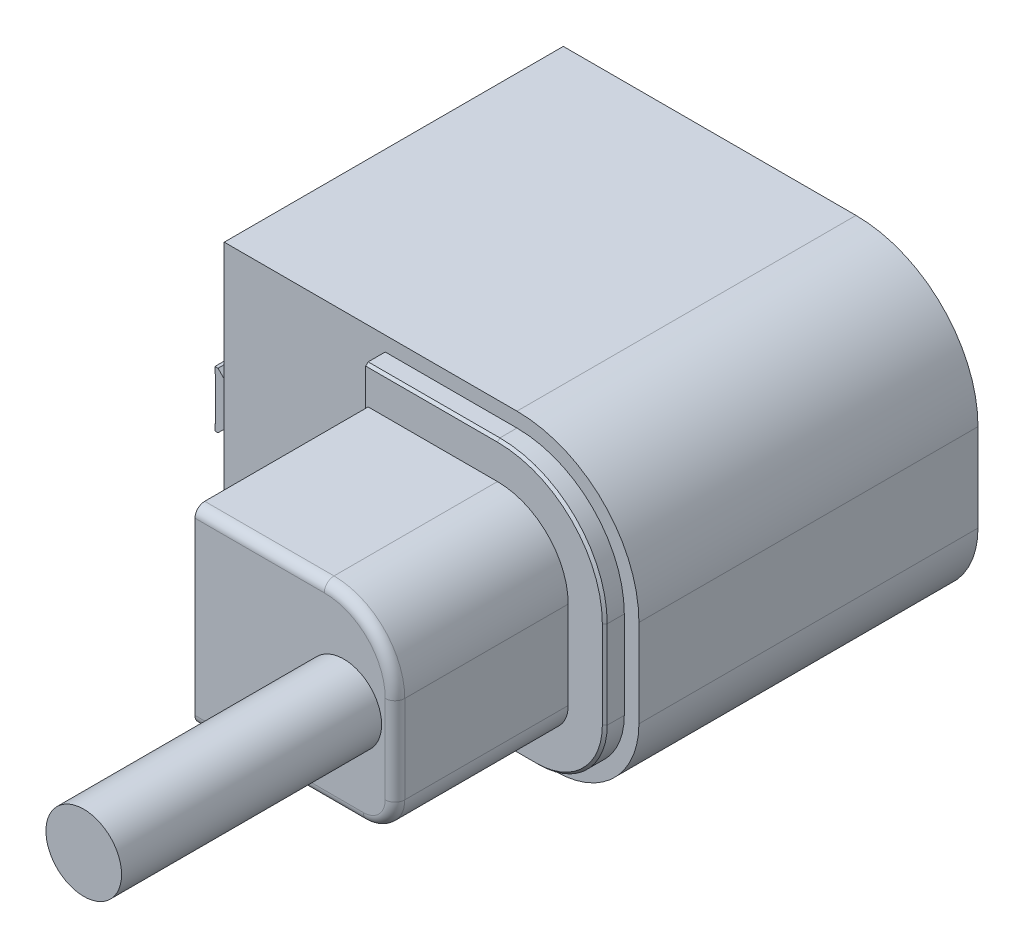
SolidWorks part; units mm, degrees
ref_plane "Front Plane" through (0, 0, 0) normal (0, 0, 1) x (1, 0, 0)
ref_plane "Top Plane" through (0, 0, 0) normal (0, 1, 0) x (1, 0, 0)
ref_plane "Right Plane" through (0, 0, 0) normal (1, 0, 0) x (0, 0, -1)
sketch "Sketch1" plane through (0, 0, 0) normal (0, 0, 1) x (1, 0, 0)
  line L0 (0, 38.0675) -> (0, -37.7433) construction
  line L1 (-42.5, 30) -> (42.5, 30)
  line L2 (42.5, 30) -> (42.5, -30)
  line L3 (42.5, -30) -> (-42.5, -30)
  line L4 (-42.5, -30) -> (-42.5, 30)
  dimension "D1" = 85
  dimension "D2" = 60
  dimension "D3" = 30
  dimension "D4" = 42.5
extrude "Boss-Extrude1" add sketch "Sketch1" along normal blind 69.5
sketch "Sketch2" plane through (0, 0, 69.5) normal (0, 0, 1) x (1, 0, 0)
  line L0 (-42.5, 0) -> (-55.2274, 0) construction
  line L1 (-42.5, 30) -> (-42.5, -30) construction
  line L6 (-42.5, 3.495) -> (-42.79, 3.495)
  line L7 (-42.79, 3.495) -> (-45.03, 5.73)
  line L8 (-45.03, 5.73) -> (-45.66, 5.73)
  line L9 (-45.66, 5.73) -> (-45.66, 4.45)
  line L10 (-45.66, 4.45) -> (-45.5331, 4.45)
  line L11 (-45.5331, 4.45) -> (-45.5331, -4.45)
  line L12 (-42.5, 3.495) -> (-42.5, -3.495)
  line L13 (-45.66, -4.45) -> (-45.5331, -4.45)
  line L14 (-45.66, -5.73) -> (-45.66, -4.45)
  line L15 (-45.03, -5.73) -> (-45.66, -5.73)
  line L16 (-42.79, -3.495) -> (-45.03, -5.73)
  line L17 (-42.5, -3.495) -> (-42.79, -3.495)
  point P14 (-45.5331, 0)
  dimension "D1" = 1.28
  dimension "D2" = 0.63
  dimension "D3" = 2.24
  dimension "D4" = 0.29
  dimension "D5" = 3.495
  dimension "D6" = 5.73
extrude "Boss-Extrude2" add sketch "Sketch2" against normal blind 66.05
sketch "Sketch3" plane through (0, -30, 0) normal (0, -1, 0) x (1, 0, 0)
  line L0 (-42.5, 69.5) -> (-42.5, 68.25)
  line L1 (-42.5, 69.5) -> (-42.5, 0) construction
  line L2 (-42.5, 68.25) -> (-45.66, 68.25)
  line L3 (-45.66, 3.45) -> (-45.66, 69.5) construction
  line L4 (-45.66, 68.25) -> (-45.66, 69.5)
  line L5 (-45.66, 69.5) -> (-42.5, 69.5)
  dimension "D1" = 1.25
extrude "Cut-Extrude1" cut sketch "Sketch3" against normal through all
sketch "Sketch4" plane through (-42.5, 0, 0) normal (-1, 0, 0) x (0, 0, 1)
  line L0 (0, 0) -> (69.5, 0) construction
  line L1 (69.5, 30) -> (69.5, -30) construction
  line L2 (3.45, 2.7) -> (14.31, 5.73)
  line L3 (3.45, 4.45) -> (3.45, -4.45) construction
  line L4 (3.45, 5.73) -> (68.25, 5.73) construction
  line L5 (14.31, 5.73) -> (3.45, 5.73)
  line L6 (3.45, 5.73) -> (3.45, 2.7)
  line L7 (3.45, -5.73) -> (3.45, -2.7)
  line L8 (14.31, -5.73) -> (3.45, -5.73)
  line L9 (3.45, -2.7) -> (14.31, -5.73)
  dimension "D1" = 10.86
  dimension "D2" = 3.03
extrude "Cut-Extrude2" cut sketch "Sketch4" along normal through all
sketch "Sketch5" plane through (0, 0, 69.5) normal (0, 0, 1) x (1, 0, 0)
  line L0 (42.5, 30) -> (-42.5, 30) construction
  line L1 (42.5, -30) -> (42.5, 30) construction
  line L2 (-42.5, -30) -> (42.5, -30) construction
  line L4 (42.5, -13) -> (42.5, -30)
  line L5 (42.5, -30) -> (25.5, -30)
  line L7 (17.5, 30) -> (42.5, 30)
  line L8 (42.5, 30) -> (42.5, 5)
  arc A0 (17.5, 30) -> (42.5, 5) centre (17.5, 5) cw
  arc A1 (42.5, -13) -> (25.5, -30) centre (25.5, -13) cw
  dimension "D3" = 25
  dimension "D6" = 17
  dimension "D1" = 25
  dimension "D2" = 25
  dimension "D4" = 17
  dimension "D5" = 17
extrude "Cut-Extrude3" cut sketch "Sketch5" against normal through all
sketch "Sketch6" plane through (0, 0, 69.5) normal (0, 0, 1) x (1, 0, 0)
  line L0 (17.5, 27) -> (-9.5, 27)
  line L1 (-9.5, 27) -> (-9.5, -27)
  line L2 (-9.5, -27) -> (17.3085, -27)
  line L3 (17.5, 30) -> (-42.5, 30) construction
  line L5 (17.3085, -27) -> (25.5, -27)
  line L6 (39.5, 5) -> (39.5, -13)
  arc A4 (39.5, 5) -> (17.5, 27) centre (17.5, 5) ccw
  arc A7 (25.5, -27) -> (39.5, -13) centre (25.5, -13) ccw
  dimension "D1" = 54
  dimension "D2" = 27
  dimension "D3" = 3
extrude "Boss-Extrude3" add sketch "Sketch6" along normal blind 4
chamfer "Chamfer1" distance 0.5 angle 45 5 edges at (8, -27, 73.5) (35.3995, -22.8995, 73.5) (39.5, -4, 73.5) (33.0563, 20.5563, 73.5) (4, 27, 73.5)
sketch "Sketch7" plane through (0, 0, 73.5) normal (0, 0, 1) x (1, 0, 0)
  line L3 (-9, 19.5) -> (-9, -19.5)
  line L4 (-9.5, 26.5) -> (-9.5, -26.5) construction
  line L6 (-9.5, -19.5) -> (25.5, -19.5)
  line L7 (32, -13) -> (32, 5)
  line L8 (17.5, 19.5) -> (-9.5, 19.5)
  line L9 (-9, -19.5) -> (25.5, -19.5)
  line L10 (32, -13) -> (32, 5)
  line L11 (17.5, 19.5) -> (-9, 19.5)
  arc A4 (25.5, -19.5) -> (32, -13) centre (25.5, -13) ccw
  arc A5 (32, 5) -> (17.5, 19.5) centre (17.5, 5) ccw
  arc A6 (25.5, -19.5) -> (32, -13) centre (25.5, -13) ccw
  arc A7 (32, 5) -> (17.5, 19.5) centre (17.5, 5) ccw
  dimension "D2" = 0.5
  dimension "D1" = 7
extrude "Boss-Extrude4" add sketch "Sketch7" along normal blind 35.5
sketch "Sketch8" plane through (0, 0, 109) normal (0, 0, 1) x (1, 0, 0)
  line L0 (32, -13) -> (32, 5) construction
  line L1 (17.5, 19.5) -> (-9, 19.5) construction
  circle A0 centre (21.5, 0) radius 7.75
  dimension "D1" = 15.5
  dimension "D2" = 10.5
  dimension "D3" = 19.5
extrude "Boss-Extrude5" add sketch "Sketch8" along normal blind 53.3 contours A0
fillet "Fillet1" radius 2 5 edges at (4.25, 19.5, 109) (27.753, 15.253, 109) (32, -4, 109) (30.0962, -17.5962, 109) (8.25, -19.5, 109)
sketch "Sketch9" plane through (-45.5331, 0, 0) normal (-1, 0, 0) x (0, 0, 1)
  line L0 (0, 0) -> (69.5, 0) construction
  line L1 (69.5, 30) -> (69.5, -30) construction
  line L2 (0, 30) -> (0, -30) construction
  circle A0 centre (55, 0) radius 2
  circle A1 centre (35, 0) radius 2
  dimension "D1" = 4
  dimension "D2" = 4
  dimension "D3" = 35
  dimension "D4" = 55
extrude "Cut-Extrude4" cut sketch "Sketch9" against normal blind 10
sketch "Sketch10" plane through (0, 0, 0) normal (0, 0, -1) x (-1, 0, 0)
  line L0 (42.5, 30) -> (42.5, -30) construction
  line L1 (42.5, -30) -> (-25.5, -30) construction
  circle A0 centre (-16.5, -4) radius 21.5
  dimension "D1" = 59
  dimension "D2" = 26
